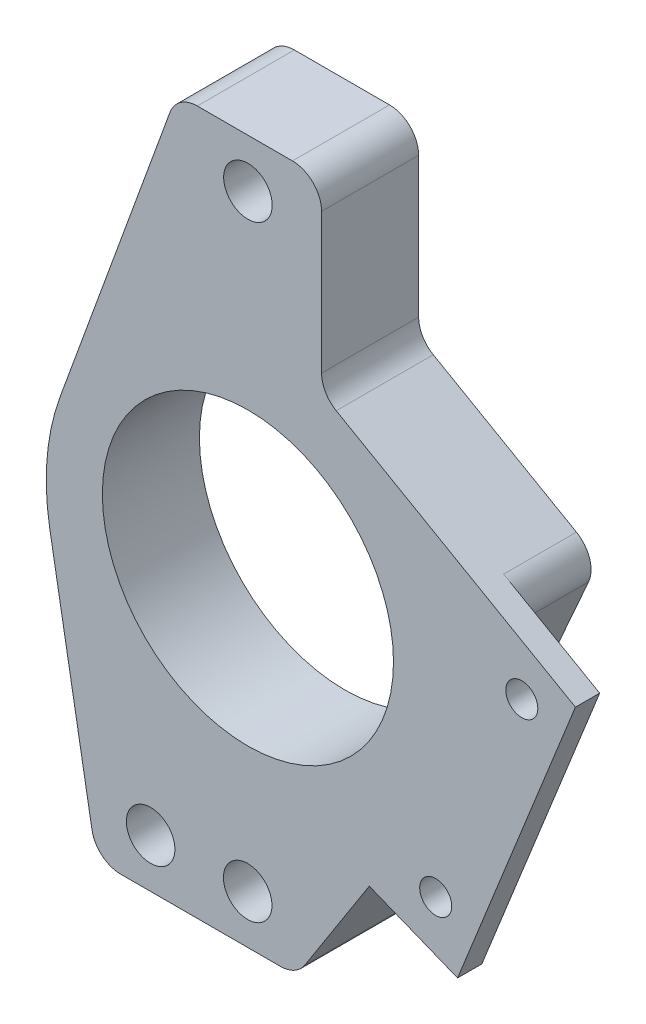
SolidWorks part; units mm, degrees
ref_plane "Front Plane" through (0, 0, 0) normal (0, 0, 1) x (1, 0, 0)
ref_plane "Top Plane" through (0, 0, 0) normal (0, 1, 0) x (1, 0, 0)
ref_plane "Right Plane" through (0, 0, 0) normal (1, 0, 0) x (0, 0, -1)
sketch "Sketch1" plane through (0, 0, 0) normal (0, 0, 1) x (1, 0, 0)
  line L0 (-18.5763, 100.3652) -> (19.2813, 100.3652)
  line L1 (19.2813, 100.3652) -> (19.2813, 51.6625)
  line L2 (19.2813, 51.6625) -> (85.7172, 13.5763)
  line L3 (85.7172, 13.5763) -> (54.8677, -63.2338)
  line L7 (12.6678, -83.786) -> (-39.7037, -83.786)
  line L9 (-39.7037, -83.786) -> (-51.867, -14.6914)
  line L13 (-49.1135, 16.6221) -> (-18.5763, 100.3652)
  line L14 (54.8677, -63.2338) -> (31.7649, -53.955)
  line L15 (31.7649, -53.955) -> (12.6678, -83.786)
  circle A0 centre (0, 0) radius 38.1
  circle A3 centre (0, 87.6652) radius 6.35
  circle A4 centre (-0.0617, -71.086) radius 6.35
  arc A5 (-49.1135, 16.6221) -> (-51.867, -14.6914) centre (7.9035, -4.1694) ccw
  circle A6 centre (-25.4617, -71.0752) radius 6.35
  dimension "D1" = 76.2
  dimension "D2" = 12.7
  dimension "D3" = 25.4
  dimension "D4" = 12.7
extrude "Boss-Extrude1" add sketch "Sketch1" along normal blind 25.4
sketch "Sketch2" plane through (0, 0, 0) normal (0, 0, 1) x (1, 0, 0)
  line L2 (85.7172, 13.5763) -> (54.8677, -63.2338)
  line L5 (85.7172, 13.5763) -> (66.5382, 24.5712)
  line L6 (85.7172, 13.5763) -> (19.2813, 51.6625) construction
  line L7 (66.5382, 24.5712) -> (31.7649, -53.955)
  line L8 (54.8677, -63.2338) -> (31.7649, -53.955)
extrude "Cut-Extrude1" cut sketch "Sketch2" along normal blind 19.05 contours L8 L7 L5 L2
sketch "Sketch3" plane through (0, 0, 25.4) normal (0, 0, 1) x (1, 0, 0)
  circle A0 centre (71.6792, 8.3618) radius 4.191
  circle A1 centre (49.1489, -47.7348) radius 4.191
  dimension "D1" = 8.382
  dimension "D2" = 8.382
  dimension "D3" = 60.452
extrude "Cut-Extrude2" cut sketch "Sketch3" against normal through all
fillet "Fillet1" radius 7.62 6 edges at (-18.5763, 100.3652, 12.7) (19.2813, 100.3652, 12.7) (19.2813, 51.6625, 12.7) (66.5382, 24.5712, 9.525) (12.6678, -83.786, 12.7) (-39.7037, -83.786, 12.7)
